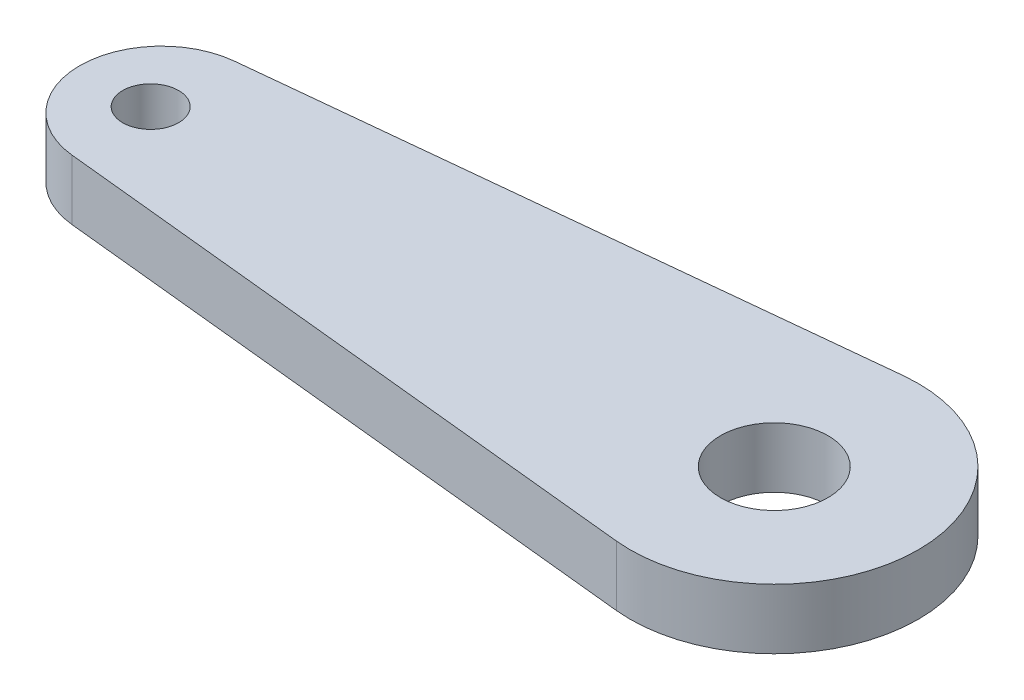
SolidWorks part; units mm, degrees
ref_plane "Front Plane" through (0, 0, 0) normal (0, 0, 1) x (1, 0, 0)
ref_plane "Top Plane" through (0, 0, 0) normal (0, 1, 0) x (1, 0, 0)
ref_plane "Right Plane" through (0, 0, 0) normal (1, 0, 0) x (0, 0, -1)
sketch "Sketch1" plane through (0, 0, 0) normal (0, 1, 0) x (1, 0, 0)
  line L1 (-14.4433, 1.8901) -> (-0.3409, 3.3326)
  line L3 (-14.4433, -1.8901) -> (-0.3409, -3.3326)
  line L4 (0, 0) -> (0, 1.25) construction
  circle A0 centre (0, 0) radius 1.25
  circle A2 centre (0, 0) radius 3.35
  circle A3 centre (-14.25, 0) radius 1.9
  circle A6 centre (-14.5, 0) radius 0.65
  point P4 (0, 0)
  point P20 (-16.15, 0)
  point P22 (3.35, 0)
  dimension "D2" = 2.5
  dimension "D3" = 1.3
  dimension "D4" = 6.7
  dimension "D5" = 3.8
  dimension "D1" = 19.5
  dimension "D6" = 14.5
extrude "Boss-Extrude1" add sketch "Sketch1" along normal blind 1.4
